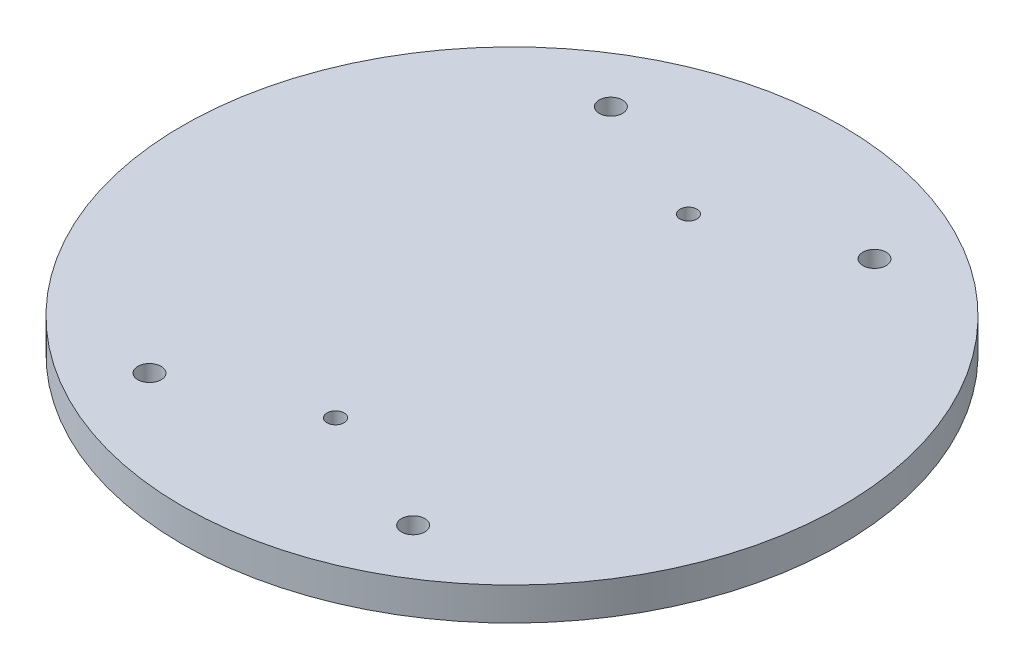
SolidWorks part; units mm, degrees
material "Plain Carbon Steel"
ref_plane "Front Plane" through (0, 0, 0) normal (0, 0, 1) x (1, 0, 0)
ref_plane "Top Plane" through (0, 0, 0) normal (0, 1, 0) x (1, 0, 0)
ref_plane "Right Plane" through (0, 0, 0) normal (1, 0, 0) x (0, 0, -1)
sketch "Sketch1" plane through (0, 0, 0) normal (0, 1, 0) x (1, 0, 0)
  circle A0 centre (0, 0) radius 63.5
  dimension "D1" = 127
extrude "Boss-Extrude1" add sketch "Sketch1" along normal blind 6.35
hole_wizard "#8 Clearance Hole1" positions "Sketch2" profile "Sketch3" hole size "#8" standard "ANSI Inch" end condition through all
sketch "Sketch2" plane through (0, 6.35, 0) normal (0, 1, 0) x (1, 0, 0)
  circle A0 centre (-25.4, -44.45) radius 1.7272 construction
  circle A1 centre (25.4, -44.45) radius 1.7272 construction
  circle A2 centre (25.4, 44.45) radius 1.7272 construction
  circle A3 centre (-25.4, 44.45) radius 1.7272 construction
  circle A4 centre (-25.4, -44.45) radius 1.7272
  circle A5 centre (25.4, -44.45) radius 1.7272
  circle A6 centre (25.4, 44.45) radius 1.7272
  circle A7 centre (-25.4, 44.45) radius 1.7272
  point P10 (-25.4, -44.45)
  point P12 (25.4, -44.45)
  point P14 (25.4, 44.45)
  point P16 (-25.4, 44.45)
sketch "Sketch3" plane through (-25.4, 6.35, 44.45) normal (1, 0, 0) x (0, 0, 1)
  line L0 (0, 0) -> (0, 6.35)
  line L1 (0, 6.35) -> (2.2479, 6.35)
  line L2 (2.2479, 6.35) -> (2.2479, 0)
  line L5 (2.2479, 0) -> (0, 0)
  line L11 (0, -6.35) -> (0, 107.95) construction
  dimension "Thru Hole Dia." = 4.4958
  dimension "Thru Hole Depth" = 6.35
hole_wizard "#8 Clearance Hole2" positions "Sketch4" profile "Sketch5" hole size "#8" standard "ANSI Inch"
sketch "Sketch4" plane through (0, 0, 0) normal (0, -1, 0) x (-1, 0, 0)
  circle A0 centre (41.275, -12.7) radius 1.7272 construction
  circle A1 centre (41.275, 12.7) radius 1.7272 construction
  circle A2 centre (-41.275, -12.7) radius 1.7272 construction
  circle A3 centre (-41.275, 12.7) radius 1.7272 construction
  circle A4 centre (41.275, -12.7) radius 1.7272
  circle A5 centre (41.275, 12.7) radius 1.7272
  circle A6 centre (-41.275, -12.7) radius 1.7272
  circle A7 centre (-41.275, 12.7) radius 1.7272
  point P1 (41.275, -12.7)
  point P3 (41.275, 12.7)
  point P5 (-41.275, -12.7)
  point P7 (-41.275, 12.7)
sketch "Sketch5" plane through (-41.275, 0, 12.7) normal (1, 0, 0) x (0, 0, -1)
  line L0 (0, 0) -> (0, 3.175)
  line L1 (0, 3.175) -> (2.2479, 3.175)
  line L2 (2.2479, 3.175) -> (2.2479, 0)
  line L5 (2.2479, 0) -> (0, 0)
  line L11 (0, -6.35) -> (0, 107.95) construction
  dimension "Thru Hole Dia." = 4.4958
  dimension "Thru Hole Depth" = 3.175
hole_wizard "Tap Drill for M4x0.7 Tap1" positions "Sketch6" profile "Sketch7" hole size "M4x0.7" standard "ANSI Metric" end condition through all
sketch "Sketch6" plane through (0, 6.35, 0) normal (0, 1, 0) x (1, 0, 0)
  line L0 (0, 34) -> (0, -34) construction
  point P1 (0, 34)
  point P2 (0, -34)
  point P5 (0, 0)
  dimension "D1" = 68
sketch "Sketch7" plane through (0, 6.35, -34) normal (1, 0, 0) x (0, 0, 1)
  line L0 (0, 0) -> (0, 6.35)
  line L1 (0, 6.35) -> (1.65, 6.35)
  line L2 (1.65, 6.35) -> (1.65, 0)
  line L5 (1.65, 0) -> (0, 0)
  line L11 (0, -6.35) -> (0, 107.95) construction
  dimension "Thru Hole Dia." = 3.3
  dimension "Thru Hole Depth" = 6.35
